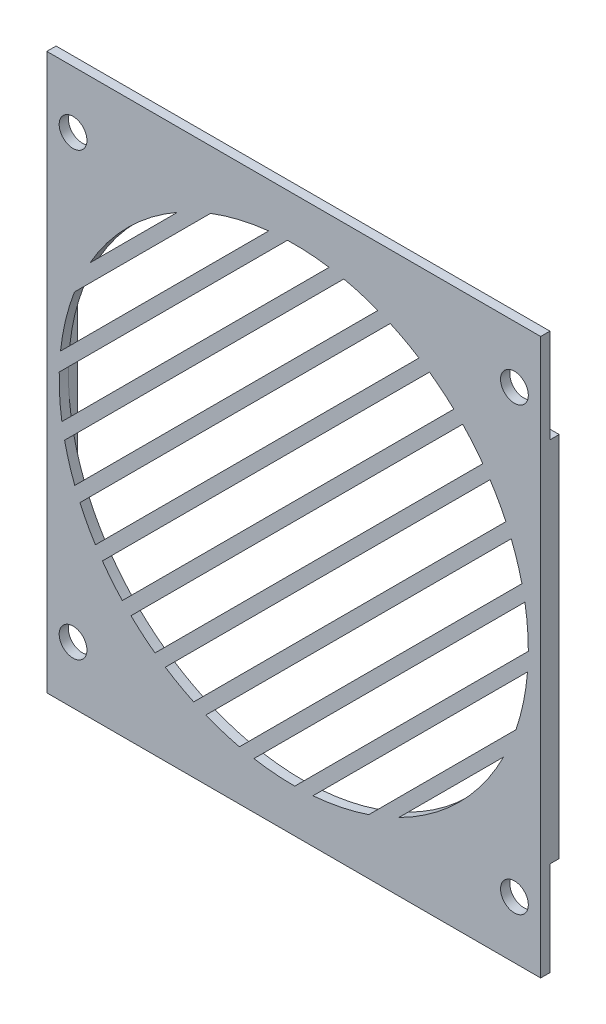
SolidWorks part; units mm, degrees
ref_plane "Front Plane" through (0, 0, 0) normal (0, 0, 1) x (1, 0, 0)
ref_plane "Top Plane" through (0, 0, 0) normal (0, 1, 0) x (1, 0, 0)
ref_plane "Right Plane" through (0, 0, 0) normal (1, 0, 0) x (0, 0, -1)
sketch "Sketch5" plane through (0, 0, 0) normal (0, 0, 1) x (1, 0, 0)
  line L1 (-40, -45) -> (40, -45)
  line L2 (-40, -45) -> (-40, 45)
  line L3 (-40, 45) -> (40, 45)
  line L4 (40, -45) -> (40, 45)
  line L5 (-40, -45) -> (40, 45) construction
  line L6 (-40, 45) -> (40, -45) construction
  point P0 (0, 0)
  dimension "D1" = 90
  dimension "D2" = 80
extrude "Boss-Extrude2" add sketch "Sketch5" along normal blind 1.5
hole_wizard "M4 Clearance Hole2" positions "Sketch6" profile "Sketch7" hole size "M4" standard "ANSI Metric" end condition through all
sketch "Sketch6" plane through (0, 0, 1.5) normal (0, 0, 1) x (1, 0, 0)
  line L1 (-35.75, -35.75) -> (35.75, -35.75)
  line L2 (-35.75, -35.75) -> (-35.75, 35.75)
  line L3 (-35.75, 35.75) -> (35.75, 35.75)
  line L4 (35.75, -35.75) -> (35.75, 35.75)
  line L5 (-35.75, -35.75) -> (35.75, 35.75) construction
  line L6 (-35.75, 35.75) -> (35.75, -35.75) construction
  point P2 (35.75, 35.75)
  point P109 (-35.75, -35.75)
  point P110 (-35.75, 35.75)
  point P111 (35.75, -35.75)
  point P116 (0, 0)
  dimension "D1" = 71.5
sketch "Sketch7" plane through (35.75, 35.75, 1.5) normal (1, 0, 0) x (0, -1, 0)
  line L0 (0, 0) -> (0, 1.5)
  line L1 (0, 1.5) -> (2.25, 1.5)
  line L2 (2.25, 1.5) -> (2.25, 0)
  line L5 (2.25, 0) -> (0, 0)
  line L11 (0, -6.35) -> (0, 107.95) construction
  dimension "Thru Hole Dia." = 4.5
  dimension "Thru Hole Depth" = 1.5
sketch "Sketch8" plane through (0, 0, 1.5) normal (0, 0, 1) x (1, 0, 0)
  circle A0 centre (0, 0) radius 38
  dimension "D1" = 76
extrude "Cut-Extrude1" cut sketch "Sketch8" against normal blind 2 contours A0
sketch "Sketch9" plane through (0, 0, 1.5) normal (0, 0, 1) x (1, 0, 0)
  line L0 (-103.6041, -41.7683) -> (-6.1428, 55.693)
  line L1 (-103.6041, -41.7683) -> (-102.1899, -43.1825)
  line L2 (-6.1428, 55.693) -> (-4.7286, 54.2787)
  line L3 (-102.1899, -43.1825) -> (-4.7286, 54.2787)
  line L4 (-103.6041, -41.7683) -> (-4.7286, 54.2787) construction
  line L5 (-6.1428, 55.693) -> (-102.1899, -43.1825) construction
  line L6 (-40, -45) -> (40, -45) construction
  line L7 (-93.6041, -41.7683) -> (3.8572, 55.693)
  line L8 (-93.6041, -41.7683) -> (-92.1899, -43.1825)
  line L9 (3.8572, 55.693) -> (5.2714, 54.2787)
  line L10 (-92.1899, -43.1825) -> (5.2714, 54.2787)
  line L11 (-93.6041, -41.7683) -> (5.2714, 54.2787) construction
  line L12 (3.8572, 55.693) -> (-92.1899, -43.1825) construction
  line L13 (-83.6041, -41.7683) -> (13.8572, 55.693)
  line L14 (-83.6041, -41.7683) -> (-82.1899, -43.1825)
  line L15 (13.8572, 55.693) -> (15.2714, 54.2787)
  line L16 (-82.1899, -43.1825) -> (15.2714, 54.2787)
  line L17 (-83.6041, -41.7683) -> (15.2714, 54.2787) construction
  line L18 (13.8572, 55.693) -> (-82.1899, -43.1825) construction
  line L19 (-73.6041, -41.7683) -> (23.8572, 55.693)
  line L20 (-73.6041, -41.7683) -> (-72.1899, -43.1825)
  line L21 (23.8572, 55.693) -> (25.2714, 54.2787)
  line L22 (-72.1899, -43.1825) -> (25.2714, 54.2787)
  line L23 (-73.6041, -41.7683) -> (25.2714, 54.2787) construction
  line L24 (23.8572, 55.693) -> (-72.1899, -43.1825) construction
  line L25 (-63.6041, -41.7683) -> (33.8572, 55.693)
  line L26 (-63.6041, -41.7683) -> (-62.1899, -43.1825)
  line L27 (33.8572, 55.693) -> (35.2714, 54.2787)
  line L28 (-62.1899, -43.1825) -> (35.2714, 54.2787)
  line L29 (-63.6041, -41.7683) -> (35.2714, 54.2787) construction
  line L30 (33.8572, 55.693) -> (-62.1899, -43.1825) construction
  line L31 (-53.6041, -41.7683) -> (43.8572, 55.693)
  line L32 (-53.6041, -41.7683) -> (-52.1899, -43.1825)
  line L33 (43.8572, 55.693) -> (45.2714, 54.2787)
  line L34 (-52.1899, -43.1825) -> (45.2714, 54.2787)
  line L35 (-53.6041, -41.7683) -> (45.2714, 54.2787) construction
  line L36 (43.8572, 55.693) -> (-52.1899, -43.1825) construction
  line L37 (-43.6041, -41.7683) -> (53.8572, 55.693)
  line L38 (-43.6041, -41.7683) -> (-42.1899, -43.1825)
  line L39 (53.8572, 55.693) -> (55.2714, 54.2787)
  line L40 (-42.1899, -43.1825) -> (55.2714, 54.2787)
  line L41 (-43.6041, -41.7683) -> (55.2714, 54.2787) construction
  line L42 (53.8572, 55.693) -> (-42.1899, -43.1825) construction
  line L43 (-33.6041, -41.7683) -> (63.8572, 55.693)
  line L44 (-33.6041, -41.7683) -> (-32.1899, -43.1825)
  line L45 (63.8572, 55.693) -> (65.2714, 54.2787)
  line L46 (-32.1899, -43.1825) -> (65.2714, 54.2787)
  line L47 (-33.6041, -41.7683) -> (65.2714, 54.2787) construction
  line L48 (63.8572, 55.693) -> (-32.1899, -43.1825) construction
  line L49 (-23.6041, -41.7683) -> (73.8572, 55.693)
  line L50 (-23.6041, -41.7683) -> (-22.1899, -43.1825)
  line L51 (73.8572, 55.693) -> (75.2714, 54.2787)
  line L52 (-22.1899, -43.1825) -> (75.2714, 54.2787)
  line L53 (-23.6041, -41.7683) -> (75.2714, 54.2787) construction
  line L54 (73.8572, 55.693) -> (-22.1899, -43.1825) construction
  line L55 (-13.6041, -41.7683) -> (83.8572, 55.693)
  line L56 (-13.6041, -41.7683) -> (-12.1899, -43.1825)
  line L57 (83.8572, 55.693) -> (85.2714, 54.2787)
  line L58 (-12.1899, -43.1825) -> (85.2714, 54.2787)
  line L59 (-13.6041, -41.7683) -> (85.2714, 54.2787) construction
  line L60 (83.8572, 55.693) -> (-12.1899, -43.1825) construction
  line L61 (-3.6041, -41.7683) -> (93.8572, 55.693)
  line L62 (-3.6041, -41.7683) -> (-2.1899, -43.1825)
  line L63 (93.8572, 55.693) -> (95.2714, 54.2787)
  line L64 (-2.1899, -43.1825) -> (95.2714, 54.2787)
  line L65 (-3.6041, -41.7683) -> (95.2714, 54.2787) construction
  line L66 (93.8572, 55.693) -> (-2.1899, -43.1825) construction
  line L67 (6.3959, -41.7683) -> (103.8572, 55.693)
  line L68 (6.3959, -41.7683) -> (7.8101, -43.1825)
  line L69 (103.8572, 55.693) -> (105.2714, 54.2787)
  line L70 (7.8101, -43.1825) -> (105.2714, 54.2787)
  line L71 (6.3959, -41.7683) -> (105.2714, 54.2787) construction
  line L72 (103.8572, 55.693) -> (7.8101, -43.1825) construction
  line L73 (16.3959, -41.7683) -> (113.8572, 55.693)
  line L74 (16.3959, -41.7683) -> (17.8101, -43.1825)
  line L75 (113.8572, 55.693) -> (115.2714, 54.2787)
  line L76 (17.8101, -43.1825) -> (115.2714, 54.2787)
  line L77 (16.3959, -41.7683) -> (115.2714, 54.2787) construction
  line L78 (113.8572, 55.693) -> (17.8101, -43.1825) construction
  line L79 (26.3959, -41.7683) -> (123.8572, 55.693)
  line L80 (26.3959, -41.7683) -> (27.8101, -43.1825)
  line L81 (123.8572, 55.693) -> (125.2714, 54.2787)
  line L82 (27.8101, -43.1825) -> (125.2714, 54.2787)
  line L83 (26.3959, -41.7683) -> (125.2714, 54.2787) construction
  line L84 (123.8572, 55.693) -> (27.8101, -43.1825) construction
  line L85 (36.3959, -41.7683) -> (133.8572, 55.693)
  line L86 (36.3959, -41.7683) -> (37.8101, -43.1825)
  line L87 (133.8572, 55.693) -> (135.2714, 54.2787)
  line L88 (37.8101, -43.1825) -> (135.2714, 54.2787)
  line L89 (36.3959, -41.7683) -> (135.2714, 54.2787) construction
  line L90 (133.8572, 55.693) -> (37.8101, -43.1825) construction
  line L91 (46.3959, -41.7683) -> (143.8572, 55.693)
  line L92 (46.3959, -41.7683) -> (47.8101, -43.1825)
  line L93 (143.8572, 55.693) -> (145.2714, 54.2787)
  line L94 (47.8101, -43.1825) -> (145.2714, 54.2787)
  line L95 (46.3959, -41.7683) -> (145.2714, 54.2787) construction
  line L96 (143.8572, 55.693) -> (47.8101, -43.1825) construction
  line L97 (56.3959, -41.7683) -> (153.8572, 55.693)
  line L98 (56.3959, -41.7683) -> (57.8101, -43.1825)
  line L99 (153.8572, 55.693) -> (155.2714, 54.2787)
  line L100 (57.8101, -43.1825) -> (155.2714, 54.2787)
  line L101 (56.3959, -41.7683) -> (155.2714, 54.2787) construction
  line L102 (153.8572, 55.693) -> (57.8101, -43.1825) construction
  line L103 (66.3959, -41.7683) -> (163.8572, 55.693)
  line L104 (66.3959, -41.7683) -> (67.8101, -43.1825)
  line L105 (163.8572, 55.693) -> (165.2714, 54.2787)
  line L106 (67.8101, -43.1825) -> (165.2714, 54.2787)
  line L107 (66.3959, -41.7683) -> (165.2714, 54.2787) construction
  line L108 (163.8572, 55.693) -> (67.8101, -43.1825) construction
  line L109 (76.3959, -41.7683) -> (173.8572, 55.693)
  line L110 (76.3959, -41.7683) -> (77.8101, -43.1825)
  line L111 (173.8572, 55.693) -> (175.2714, 54.2787)
  line L112 (77.8101, -43.1825) -> (175.2714, 54.2787)
  line L113 (76.3959, -41.7683) -> (175.2714, 54.2787) construction
  line L114 (173.8572, 55.693) -> (77.8101, -43.1825) construction
  line L115 (86.3959, -41.7683) -> (183.8572, 55.693)
  line L116 (86.3959, -41.7683) -> (87.8101, -43.1825)
  line L117 (183.8572, 55.693) -> (185.2714, 54.2787)
  line L118 (87.8101, -43.1825) -> (185.2714, 54.2787)
  line L119 (86.3959, -41.7683) -> (185.2714, 54.2787) construction
  line L120 (183.8572, 55.693) -> (87.8101, -43.1825) construction
  circle A0 centre (0, 0) radius 38
  point P1 (-54.1663, 6.2552)
  point P9 (-44.1663, 6.2552)
  point P14 (-34.1663, 6.2552)
  point P19 (-24.1663, 6.2552)
  point P24 (-14.1663, 6.2552)
  point P29 (-4.1663, 6.2552)
  point P34 (5.8337, 6.2552)
  point P39 (15.8337, 6.2552)
  point P44 (25.8337, 6.2552)
  point P49 (35.8337, 6.2552)
  point P54 (45.8337, 6.2552)
  point P59 (55.8337, 6.2552)
  point P64 (65.8337, 6.2552)
  point P69 (75.8337, 6.2552)
  point P74 (85.8337, 6.2552)
  point P79 (95.8337, 6.2552)
  point P84 (105.8337, 6.2552)
  point P89 (115.8337, 6.2552)
  point P94 (125.8337, 6.2552)
  point P99 (135.8337, 6.2552)
  circle M142 centre (0, 0) radius 38
  dimension "D1" = 2
  dimension "D2" = 45
  dimension "D3" = 20
extrude "Boss-Extrude3" add sketch "Sketch9" against normal blind 1.5 contours L10 L7 M142 | L16 L13 M142 | L22 L19 M142 | L28 L25 M142 | L34 L31 M142 | L40 L37 M142 | L46 L43 M142 | L52 L49 M142 | L58 L55 M142 | L64 L61 M142 | L70 L67 M142
sketch "Sketch10" plane through (0, 0, 0) normal (0, 0, -1) x (-1, 0, 0)
  line L0 (40, 45) -> (40, -45) construction
  line L1 (-40, -29.75) -> (40, -29.75)
  line L2 (-40, -29.75) -> (-40, 29.75)
  line L3 (-40, 29.75) -> (40, 29.75)
  line L4 (40, -29.75) -> (40, 29.75)
  line L5 (-40, -29.75) -> (40, 29.75) construction
  line L6 (-40, 29.75) -> (40, -29.75) construction
  line L7 (-40, 45) -> (40, 45) construction
  line L8 (-38, -29.75) -> (-38, 29.75)
  line L9 (38, 29.75) -> (38, -29.75)
  point P0 (0, 0)
  dimension "D1" = 15.25
  dimension "D2" = 2
  dimension "D3" = 2
extrude "Boss-Extrude4" add sketch "Sketch10" along normal blind 1.5 contours L1 L8 L3 L2 | L3 L9 L1 L4
